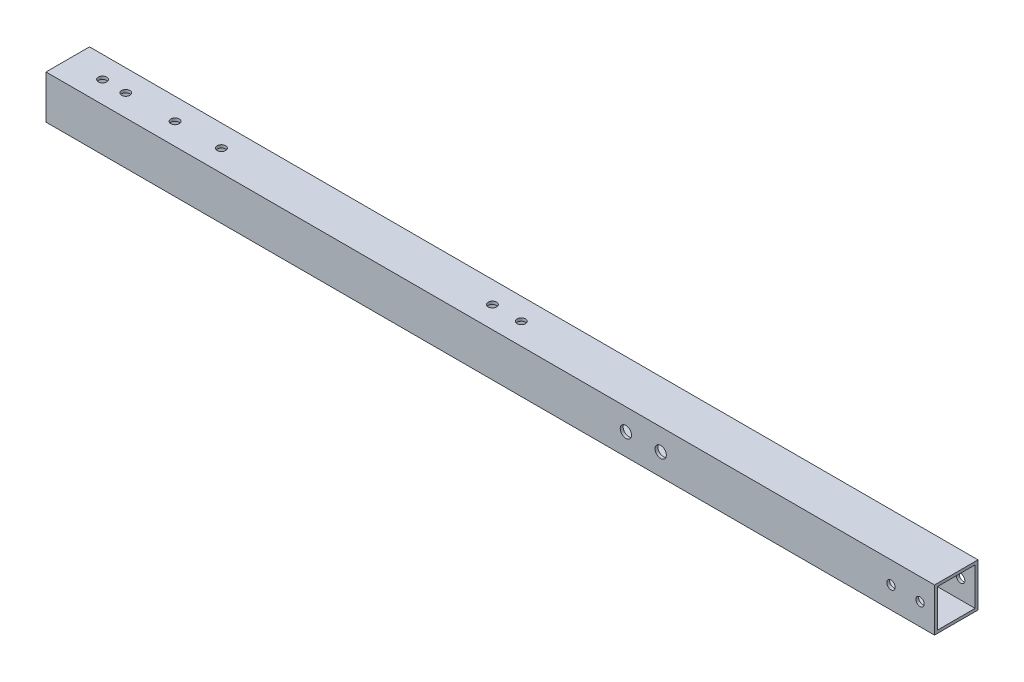
SolidWorks part; units mm, degrees
material "Thornel Mat VMA"
ref_plane "前视基准面" through (0, 0, 0) normal (0, 0, 1) x (1, 0, 0)
ref_plane "上视基准面" through (0, 0, 0) normal (0, 1, 0) x (1, 0, 0)
ref_plane "右视基准面" through (0, 0, 0) normal (1, 0, 0) x (0, 0, -1)
other "Configuration Table"
sketch "草图1" plane through (0, 0, 0) normal (1, 0, 0) x (0, 0, -1)
  line L0 (-6.5, -6.5) -> (-6.5, 6.5)
  line L1 (-7.5, -7.5) -> (7.5, -7.5)
  line L2 (-7.5, -7.5) -> (-7.5, 7.5)
  line L3 (-7.5, 7.5) -> (7.5, 7.5)
  line L4 (7.5, -7.5) -> (7.5, 7.5)
  line L5 (-7.5, -7.5) -> (7.5, 7.5) construction
  line L6 (-7.5, 7.5) -> (7.5, -7.5) construction
  line L7 (-6.5, 6.5) -> (6.5, 6.5)
  line L8 (6.5, -6.5) -> (6.5, 6.5)
  line L9 (-6.5, -6.5) -> (6.5, -6.5)
  point P0 (0, 0)
  dimension "D1" = 15
  dimension "D2" = 15
  dimension "D3" = 1
extrude "凸台-拉伸1" add sketch "草图1" along normal blind 306.44
sketch "草图2" plane through (0, 7.5, 0) normal (0, 1, 0) x (1, 0, 0)
  line L0 (-96.8587, 0) -> (354.0801, 0) construction
  line L1 (306.44, -7.5) -> (306.44, 7.5) construction
  circle A0 centre (20, 0) radius 1.45 construction
  circle A1 centre (12, 0) radius 1.45 construction
  circle A2 centre (20, 0) radius 1.45
  circle A3 centre (12, 0) radius 1.45
  circle A4 centre (37, 0) radius 1.45 construction
  circle A5 centre (37, 0) radius 1.45
  circle A6 centre (53, 0) radius 1.45 construction
  circle A7 centre (53, 0) radius 1.45
  circle A8 centre (156.44, 0) radius 1.45
  circle A9 centre (146.44, 0) radius 1.45
  dimension "D2" = 2.9
  dimension "D3" = 160
  dimension "D1" = 150
extrude "切除-拉伸1" cut sketch "草图2" against normal through all
sketch "草图3" plane through (0, 0, 7.5) normal (0, 0, 1) x (1, 0, 0)
  line L0 (0, 0) -> (338.4732, 0) construction
  circle A0 centre (301.44, 0) radius 1.45 construction
  circle A1 centre (291.44, 0) radius 1.45 construction
  circle A2 centre (301.44, 0) radius 1.45
  circle A3 centre (291.44, 0) radius 1.45
  circle A4 centre (200, 0) radius 1.95
  circle A5 centre (212, 0) radius 1.95
  dimension "D1" = 200
  dimension "D3" = 3.9
  dimension "D4" = 3.9
  dimension "D2" = 212
extrude "切除-拉伸2" cut sketch "草图3" against normal through all
